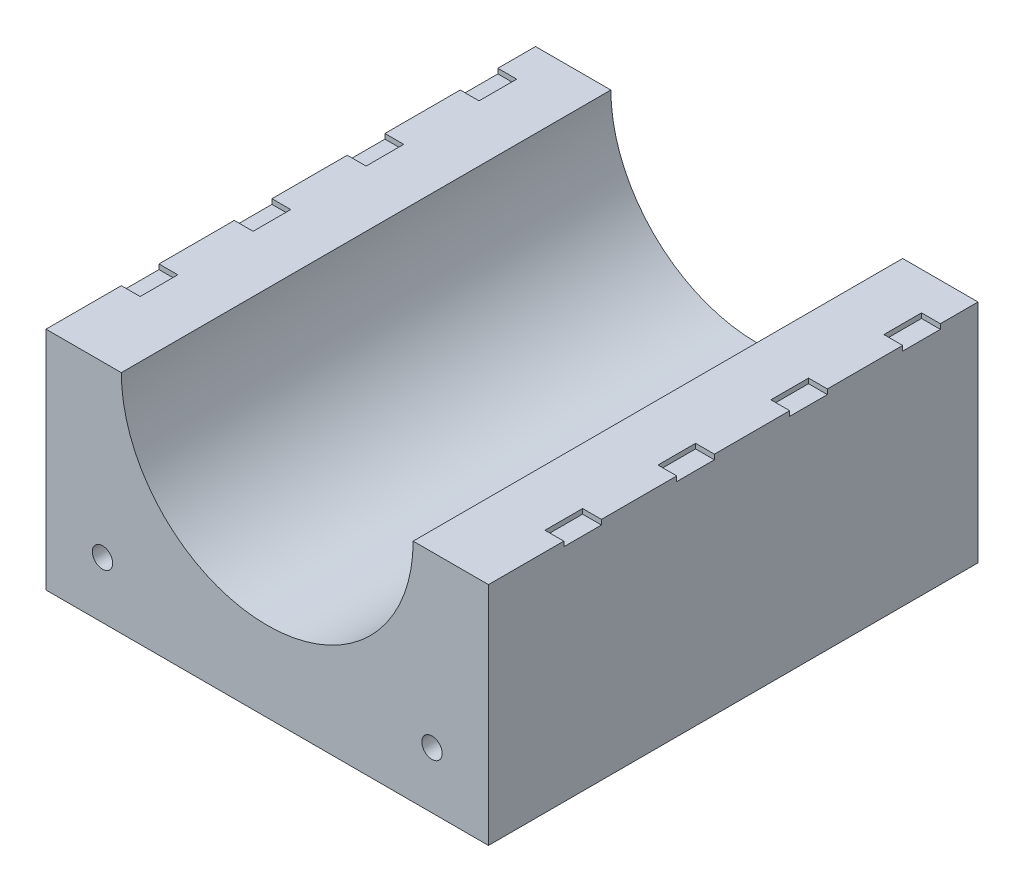
SolidWorks part; units mm, degrees
ref_plane "Front Plane" through (0, 0, 0) normal (0, 0, 1) x (1, 0, 0)
ref_plane "Top Plane" through (0, 0, 0) normal (0, 1, 0) x (1, 0, 0)
ref_plane "Right Plane" through (0, 0, 0) normal (1, 0, 0) x (0, 0, -1)
sketch "Sketch1" plane through (0, 0, 0) normal (0, 0, 1) x (1, 0, 0)
  line L0 (-49.2125, 0) -> (-74.6125, 0)
  line L1 (-74.6125, 0) -> (-74.6125, -76.2)
  line L2 (-74.6125, -76.2) -> (74.6125, -76.2)
  line L3 (74.6125, -76.2) -> (74.6125, 0)
  line L4 (74.6125, 0) -> (49.2125, 0)
  arc A0 (-49.2125, 0) -> (49.2125, 0) centre (0, 0) ccw
  circle A1 centre (-55.5625, -57.15) radius 3.429
  circle A2 centre (55.5625, -57.15) radius 3.429
  dimension "D1" = 98.425
  dimension "D5" = 6.858
  dimension "D6" = 6.858
  dimension "D2" = 25.4
  dimension "D3" = 25.4
  dimension "D4" = 76.2
  dimension "D7" = 19.05
  dimension "D8" = 19.05
  dimension "D9" = 19.05
  dimension "D10" = 19.05
extrude "Boss-Extrude1" add sketch "Sketch1" along normal blind 165.1
sketch "Sketch2" plane through (0, 0, 0) normal (0, 0, -1) x (-1, 0, 0)
  line L0 (-61.9125, 0) -> (-61.9125, -76.2) construction
  line L1 (-74.6125, 0) -> (-49.2125, 0) construction
  line L2 (74.6125, -76.2) -> (-74.6125, -76.2) construction
  line L3 (61.9125, 0) -> (61.9125, -76.2) construction
  line L4 (49.2125, 0) -> (74.6125, 0) construction
  line L5 (74.6125, -63.5) -> (-74.6125, -63.5) construction
  line L6 (74.6125, 0) -> (74.6125, -76.2) construction
  line L7 (-74.6125, -76.2) -> (-74.6125, 0) construction
  line L8 (0, -49.2125) -> (0, -76.2) construction
  line L9 (-68.2625, -12.7) -> (-55.5625, -12.7)
  line L10 (-68.2625, -12.7) -> (-68.2625, -25.4)
  line L11 (-68.2625, -25.4) -> (-55.5625, -25.4)
  line L12 (-55.5625, -12.7) -> (-55.5625, -25.4)
  line L13 (-6.35, -57.15) -> (6.35, -57.15)
  line L14 (-6.35, -57.15) -> (-6.35, -69.85)
  line L15 (-6.35, -69.85) -> (6.35, -69.85)
  line L16 (6.35, -57.15) -> (6.35, -69.85)
  line L17 (55.5625, -12.7) -> (68.2625, -12.7)
  line L18 (55.5625, -12.7) -> (55.5625, -25.4)
  line L19 (55.5625, -25.4) -> (68.2625, -25.4)
  line L20 (68.2625, -12.7) -> (68.2625, -25.4)
  line L21 (0, -57.15) -> (0, -69.85) construction
  arc A0 (-49.2125, 0) -> (49.2125, 0) centre (0, 0) ccw construction
  dimension "D1" = 12.7
  dimension "D2" = 12.7
  dimension "D3" = 12.7
  dimension "D4" = 12.7
  dimension "D5" = 12.7
  dimension "D6" = 12.7
  dimension "D7" = 12.7
  dimension "D8" = 6.35
  dimension "D9" = 12.7
  dimension "D10" = 12.7
  dimension "D11" = 6.35
  dimension "D12" = 6.35
extrude "Boss-Extrude2" add sketch "Sketch2" along normal blind 6.35 draft 45
sketch "Sketch3" plane through (0, 0, 0) normal (0, 1, 0) x (1, 0, 0)
  line L0 (74.6125, -165.1) -> (74.6125, 0) construction
  line L1 (74.6125, -12.7) -> (68.2625, -12.7)
  line L2 (74.6125, -12.7) -> (74.6125, -25.4)
  line L3 (74.6125, -25.4) -> (68.2625, -25.4)
  line L4 (68.2625, -12.7) -> (68.2625, -25.4)
  line L5 (74.6125, 0) -> (49.2125, 0) construction
  line L6 (74.6125, -50.8) -> (68.2625, -50.8)
  line L7 (74.6125, -50.8) -> (74.6125, -63.5)
  line L8 (74.6125, -63.5) -> (68.2625, -63.5)
  line L9 (68.2625, -50.8) -> (68.2625, -63.5)
  line L10 (74.6125, -88.9) -> (68.2625, -88.9)
  line L11 (74.6125, -88.9) -> (74.6125, -101.6)
  line L12 (74.6125, -101.6) -> (68.2625, -101.6)
  line L13 (68.2625, -88.9) -> (68.2625, -101.6)
  line L14 (74.6125, -127) -> (68.2625, -127)
  line L15 (74.6125, -127) -> (74.6125, -139.7)
  line L16 (74.6125, -139.7) -> (68.2625, -139.7)
  line L17 (68.2625, -127) -> (68.2625, -139.7)
  line L18 (-68.2625, -50.8) -> (-74.6125, -50.8)
  line L19 (-68.2625, -50.8) -> (-68.2625, -63.5)
  line L20 (-68.2625, -63.5) -> (-74.6125, -63.5)
  line L21 (-74.6125, -50.8) -> (-74.6125, -63.5)
  line L22 (-68.2625, -88.9) -> (-74.6125, -88.9)
  line L23 (-68.2625, -88.9) -> (-68.2625, -101.6)
  line L24 (-68.2625, -101.6) -> (-74.6125, -101.6)
  line L25 (-74.6125, -88.9) -> (-74.6125, -101.6)
  line L26 (-68.2625, -127) -> (-74.6125, -127)
  line L27 (-68.2625, -127) -> (-68.2625, -139.7)
  line L28 (-68.2625, -139.7) -> (-74.6125, -139.7)
  line L29 (-74.6125, -127) -> (-74.6125, -139.7)
  line L30 (-68.2625, -12.7) -> (-74.6125, -12.7)
  line L31 (-68.2625, -12.7) -> (-68.2625, -25.4)
  line L32 (-68.2625, -25.4) -> (-74.6125, -25.4)
  line L33 (-74.6125, -12.7) -> (-74.6125, -25.4)
  dimension "D1" = 6.35
  dimension "D2" = 12.7
  dimension "D3" = 12.7
  dimension "D4" = 4
  dimension "D5" = 2
extrude "Cut-Extrude1" cut sketch "Sketch3" against normal blind 1.651
